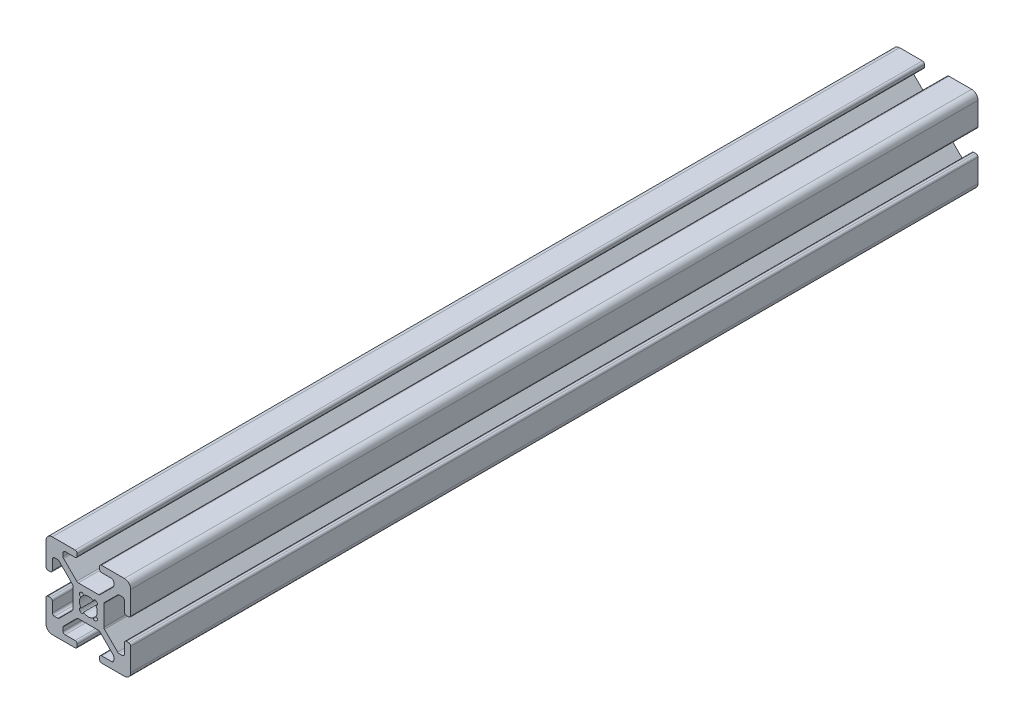
SolidWorks part; units mm, degrees
material "6061-T6 (SS)"
ref_plane "Front Plane" through (0, 0, 0) normal (0, 0, 1) x (1, 0, 0)
ref_plane "Top Plane" through (0, 0, 0) normal (0, 1, 0) x (1, 0, 0)
ref_plane "Right Plane" through (0, 0, 0) normal (1, 0, 0) x (0, 0, -1)
sketch "Sketch1" plane through (0, 0, 0) normal (0, 0, 1) x (1, 0, 0)
  line L0 (-3.655, 0) -> (-3.655, 2.3839)
  line L1 (-8.5, 3.138) -> (-8.5, 5.487)
  line L2 (-7.992, 5.995) -> (-7.2661, 5.995)
  line L3 (-9.008, 2.63) -> (-9.492, 2.63)
  line L4 (-10, 3.138) -> (-10, 8.5)
  line L5 (-8.5, 10) -> (-3.138, 10)
  line L6 (-2.63, 9.492) -> (-2.63, 9.008)
  line L7 (-3.138, 8.5) -> (-5.487, 8.5)
  line L8 (-6.9069, 5.8462) -> (-3.8038, 2.7431)
  line L9 (-5.995, 7.992) -> (-5.995, 7.2661)
  line L10 (-5.8462, 6.9069) -> (-2.7431, 3.8038)
  line L11 (-2.3839, 3.655) -> (0, 3.655)
  line L12 (-10, 10) -> (0, 0) construction
  line L13 (-3.655, 0) -> (-2.096, 0) construction
  line L14 (0, 0) -> (0, 2.096) construction
  line L15 (-1.7504, 1.5704) -> (-1.5704, 1.7504) construction
  line L16 (-2.0287, 1.8487) -> (-1.8487, 2.0287)
  line L17 (-2.096, 0) -> (0, 0) construction
  line L18 (0, 2.096) -> (0, 3.655) construction
  line L19 (3.138, 10) -> (8.5, 10)
  line L20 (2.63, 9.008) -> (2.63, 9.492)
  line L21 (3.138, 8.5) -> (5.487, 8.5)
  line L22 (5.995, 7.992) -> (5.995, 7.2661)
  line L23 (5.8462, 6.9069) -> (2.7431, 3.8038)
  line L24 (0, 3.655) -> (2.3839, 3.655)
  line L25 (1.8487, 2.0287) -> (2.0287, 1.8487)
  line L26 (3.655, 2.3839) -> (3.655, 0)
  line L27 (6.9069, 5.8462) -> (3.8038, 2.7431)
  line L28 (7.992, 5.995) -> (7.2661, 5.995)
  line L29 (8.5, 3.138) -> (8.5, 5.487)
  line L30 (9.492, 2.63) -> (9.008, 2.63)
  line L31 (10, 8.5) -> (10, 3.138)
  line L32 (10, -3.138) -> (10, -8.5)
  line L33 (9.008, -2.63) -> (9.492, -2.63)
  line L34 (8.5, -3.138) -> (8.5, -5.487)
  line L35 (7.992, -5.995) -> (7.2661, -5.995)
  line L36 (6.9069, -5.8462) -> (3.8038, -2.7431)
  line L37 (3.655, 0) -> (3.655, -2.3839)
  line L38 (2.0287, -1.8487) -> (1.8487, -2.0287)
  line L39 (2.3839, -3.655) -> (0, -3.655)
  line L40 (5.8462, -6.9069) -> (2.7431, -3.8038)
  line L41 (5.995, -7.992) -> (5.995, -7.2661)
  line L42 (3.138, -8.5) -> (5.487, -8.5)
  line L43 (2.63, -9.492) -> (2.63, -9.008)
  line L44 (8.5, -10) -> (3.138, -10)
  line L45 (-3.138, -10) -> (-8.5, -10)
  line L46 (-2.63, -9.008) -> (-2.63, -9.492)
  line L47 (-3.138, -8.5) -> (-5.487, -8.5)
  line L48 (-5.995, -7.992) -> (-5.995, -7.2661)
  line L49 (-5.8462, -6.9069) -> (-2.7431, -3.8038)
  line L50 (0, -3.655) -> (-2.3839, -3.655)
  line L51 (-1.8487, -2.0287) -> (-2.0287, -1.8487)
  line L52 (-3.655, -2.3839) -> (-3.655, 0)
  line L53 (-6.9069, -5.8462) -> (-3.8038, -2.7431)
  line L54 (-7.992, -5.995) -> (-7.2661, -5.995)
  line L55 (-8.5, -3.138) -> (-8.5, -5.487)
  line L56 (-9.492, -2.63) -> (-9.008, -2.63)
  line L57 (-10, -8.5) -> (-10, -3.138)
  arc A0 (-10, 8.5) -> (-8.5, 10) centre (-8.5, 8.5) cw
  arc A1 (-5.995, 7.2661) -> (-5.8462, 6.9069) centre (-5.487, 7.2661) ccw
  arc A2 (-2.7431, 3.8038) -> (-2.3839, 3.655) centre (-2.3839, 4.163) ccw
  arc A3 (-3.655, 2.3839) -> (-3.8038, 2.7431) centre (-4.163, 2.3839) ccw
  arc A4 (-7.2661, 5.995) -> (-6.9069, 5.8462) centre (-7.2661, 5.487) cw
  arc A5 (-8.5, 5.487) -> (-7.992, 5.995) centre (-7.992, 5.487) cw
  arc A6 (-5.487, 8.5) -> (-5.995, 7.992) centre (-5.487, 7.992) ccw
  arc A7 (-3.138, 10) -> (-2.63, 9.492) centre (-3.138, 9.492) cw
  arc A8 (-2.63, 9.008) -> (-3.138, 8.5) centre (-3.138, 9.008) cw
  arc A9 (-8.5, 3.138) -> (-9.008, 2.63) centre (-9.008, 3.138) cw
  arc A10 (-9.492, 2.63) -> (-10, 3.138) centre (-9.492, 3.138) cw
  arc A11 (0, 2.096) -> (-1.1773, 1.7341) centre (0, 0) ccw
  arc A12 (-2.0287, 1.8487) -> (-1.7341, 1.1773) centre (-1.7504, 1.5704) ccw
  arc A13 (-1.1773, 1.7341) -> (-1.8487, 2.0287) centre (-1.5704, 1.7504) ccw
  arc A14 (-1.7341, 1.1773) -> (-2.096, 0) centre (0, 0) ccw
  arc A15 (8.5, 10) -> (10, 8.5) centre (8.5, 8.5) cw
  arc A16 (2.63, 9.492) -> (3.138, 10) centre (3.138, 9.492) cw
  arc A17 (3.138, 8.5) -> (2.63, 9.008) centre (3.138, 9.008) cw
  arc A18 (5.487, 8.5) -> (5.995, 7.992) centre (5.487, 7.992) cw
  arc A19 (5.995, 7.2661) -> (5.8462, 6.9069) centre (5.487, 7.2661) cw
  arc A20 (2.3839, 3.655) -> (2.7431, 3.8038) centre (2.3839, 4.163) ccw
  arc A21 (1.1773, 1.7341) -> (0, 2.096) centre (0, 0) ccw
  arc A22 (1.8487, 2.0287) -> (1.1773, 1.7341) centre (1.5704, 1.7504) ccw
  arc A23 (1.7341, 1.1773) -> (2.0287, 1.8487) centre (1.7504, 1.5704) ccw
  arc A24 (2.096, 0) -> (1.7341, 1.1773) centre (0, 0) ccw
  arc A25 (3.8038, 2.7431) -> (3.655, 2.3839) centre (4.163, 2.3839) ccw
  arc A26 (7.2661, 5.995) -> (6.9069, 5.8462) centre (7.2661, 5.487) ccw
  arc A27 (8.5, 5.487) -> (7.992, 5.995) centre (7.992, 5.487) ccw
  arc A28 (9.008, 2.63) -> (8.5, 3.138) centre (9.008, 3.138) cw
  arc A29 (10, 3.138) -> (9.492, 2.63) centre (9.492, 3.138) cw
  arc A30 (10, -8.5) -> (8.5, -10) centre (8.5, -8.5) cw
  arc A31 (9.492, -2.63) -> (10, -3.138) centre (9.492, -3.138) cw
  arc A32 (8.5, -3.138) -> (9.008, -2.63) centre (9.008, -3.138) cw
  arc A33 (8.5, -5.487) -> (7.992, -5.995) centre (7.992, -5.487) cw
  arc A34 (7.2661, -5.995) -> (6.9069, -5.8462) centre (7.2661, -5.487) cw
  arc A35 (3.655, -2.3839) -> (3.8038, -2.7431) centre (4.163, -2.3839) ccw
  arc A36 (1.7341, -1.1773) -> (2.096, 0) centre (0, 0) ccw
  arc A37 (2.0287, -1.8487) -> (1.7341, -1.1773) centre (1.7504, -1.5704) ccw
  arc A38 (1.1773, -1.7341) -> (1.8487, -2.0287) centre (1.5704, -1.7504) ccw
  arc A39 (0, -2.096) -> (1.1773, -1.7341) centre (0, 0) ccw
  arc A40 (2.7431, -3.8038) -> (2.3839, -3.655) centre (2.3839, -4.163) ccw
  arc A41 (5.995, -7.2661) -> (5.8462, -6.9069) centre (5.487, -7.2661) ccw
  arc A42 (5.487, -8.5) -> (5.995, -7.992) centre (5.487, -7.992) ccw
  arc A43 (2.63, -9.008) -> (3.138, -8.5) centre (3.138, -9.008) cw
  arc A44 (3.138, -10) -> (2.63, -9.492) centre (3.138, -9.492) cw
  arc A45 (-8.5, -10) -> (-10, -8.5) centre (-8.5, -8.5) cw
  arc A46 (-2.63, -9.492) -> (-3.138, -10) centre (-3.138, -9.492) cw
  arc A47 (-3.138, -8.5) -> (-2.63, -9.008) centre (-3.138, -9.008) cw
  arc A48 (-5.487, -8.5) -> (-5.995, -7.992) centre (-5.487, -7.992) cw
  arc A49 (-5.995, -7.2661) -> (-5.8462, -6.9069) centre (-5.487, -7.2661) cw
  arc A50 (-2.3839, -3.655) -> (-2.7431, -3.8038) centre (-2.3839, -4.163) ccw
  arc A51 (-1.1773, -1.7341) -> (0, -2.096) centre (0, 0) ccw
  arc A52 (-1.8487, -2.0287) -> (-1.1773, -1.7341) centre (-1.5704, -1.7504) ccw
  arc A53 (-1.7341, -1.1773) -> (-2.0287, -1.8487) centre (-1.7504, -1.5704) ccw
  arc A54 (-2.096, 0) -> (-1.7341, -1.1773) centre (0, 0) ccw
  arc A55 (-3.8038, -2.7431) -> (-3.655, -2.3839) centre (-4.163, -2.3839) ccw
  arc A56 (-7.2661, -5.995) -> (-6.9069, -5.8462) centre (-7.2661, -5.487) ccw
  arc A57 (-8.5, -5.487) -> (-7.992, -5.995) centre (-7.992, -5.487) ccw
  arc A58 (-9.008, -2.63) -> (-8.5, -3.138) centre (-9.008, -3.138) cw
  arc A59 (-10, -3.138) -> (-9.492, -2.63) centre (-9.492, -3.138) cw
  point P19 (-1.6604, 1.6604)
  dimension "D7" = 1.5
  dimension "D8" = 0.508
  dimension "D9" = 2.096
  dimension "D10" = 0.787
  dimension "D1" = 10
  dimension "D2" = 2.63
  dimension "D3" = 4.845
  dimension "D4" = 1.5
  dimension "D5" = 1.5
  dimension "D6" = 5.995
  dimension "D11" = 2.3482
  dimension "D12" = 0.2546
  dimension "D13" = 4
extrude "2020 Profile" add sketch "Sketch1" along normal mid plane 200
